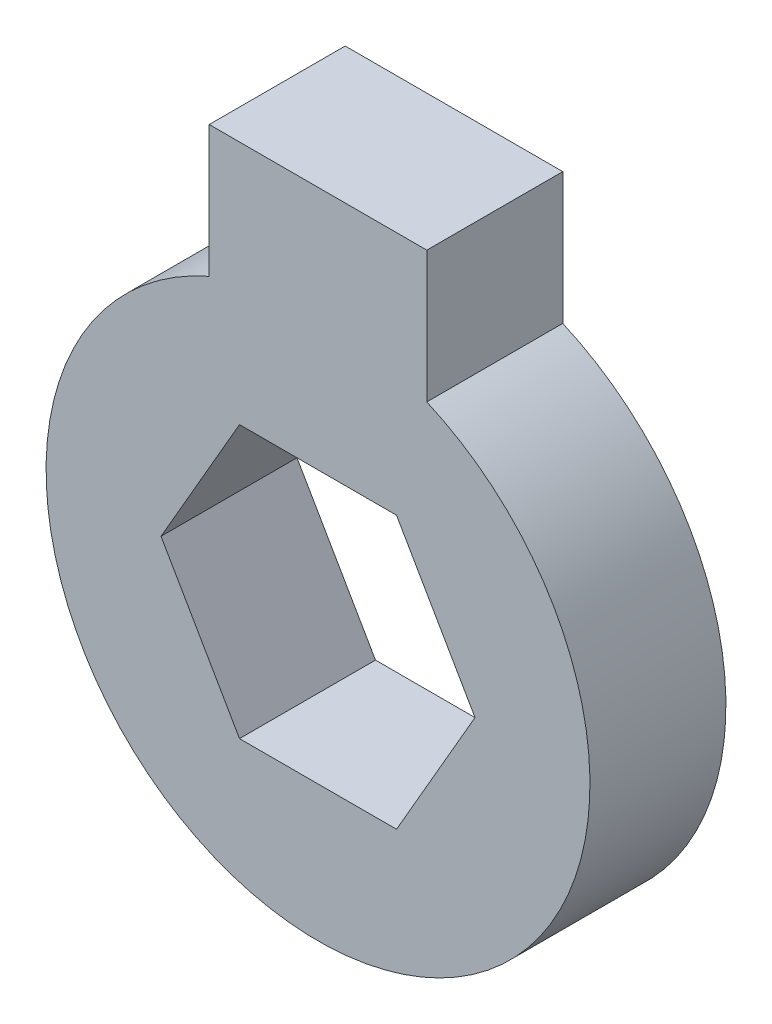
SolidWorks part; units mm, degrees
ref_plane "Front Plane" through (0, 0, 0) normal (0, 0, 1) x (1, 0, 0)
ref_plane "Top Plane" through (0, 0, 0) normal (0, 1, 0) x (1, 0, 0)
ref_plane "Right Plane" through (0, 0, 0) normal (1, 0, 0) x (0, 0, -1)
sketch "Sketch1" plane through (0, 0, 0) normal (0, 0, 1) x (1, 0, 0)
  line L0 (-5.08, 17.78) -> (5.08, 17.78)
  line L1 (7.3323, 0) -> (3.6662, 6.35)
  line L2 (3.6662, 6.35) -> (-3.6662, 6.35)
  line L3 (-3.6662, 6.35) -> (-7.3323, 0)
  line L4 (-7.3323, 0) -> (-3.6662, -6.35)
  line L5 (-3.6662, -6.35) -> (3.6662, -6.35)
  line L6 (3.6662, -6.35) -> (7.3323, 0)
  line L7 (-5.08, 17.78) -> (-5.08, 11.6397)
  line L8 (5.08, 17.78) -> (5.08, 11.6397)
  circle A0 centre (0, 0) radius 6.35 construction
  arc A1 (-5.08, 11.6397) -> (5.08, 11.6397) centre (0, 0) ccw
  arc A2 (5.08, 11.6397) -> (-5.08, 11.6397) centre (0, 0) ccw construction
  point P12 (0, 17.78)
  dimension "D2" = 25.4
  dimension "D1" = 12.7
  dimension "D3" = 10.16
  dimension "D4" = 17.78
extrude "Boss-Extrude1" add sketch "Sketch1" along normal blind 6.35
